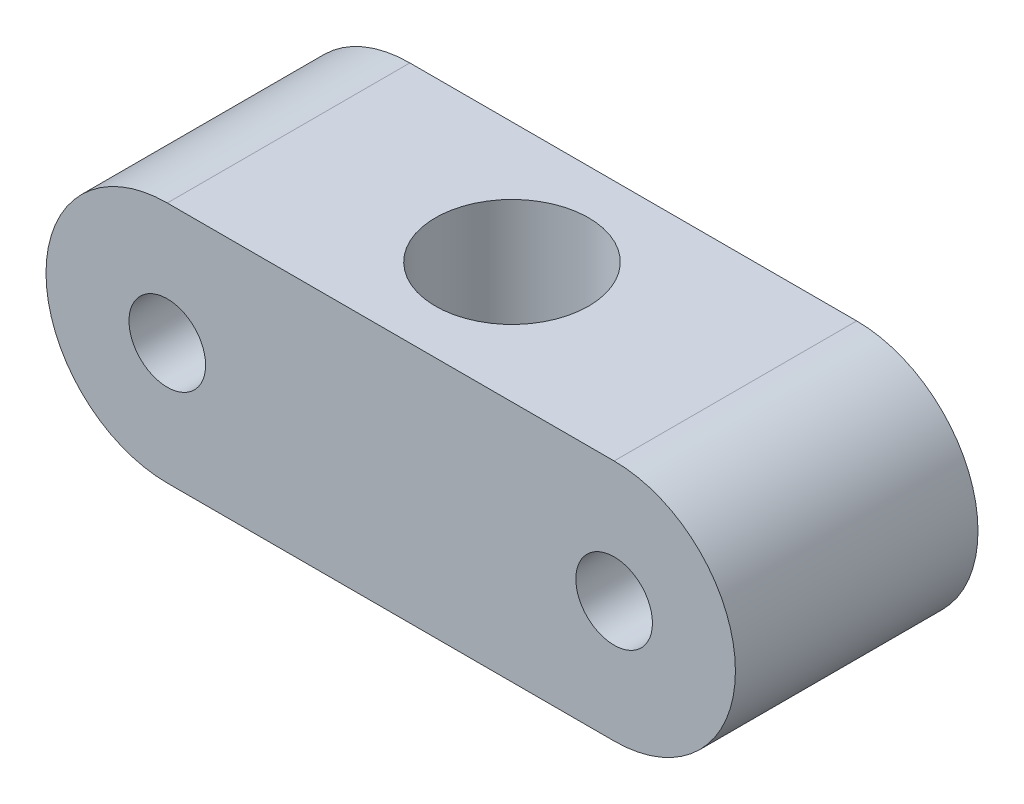
SolidWorks part; units mm, degrees
ref_plane "Front Plane" through (0, 0, 0) normal (0, 0, 1) x (1, 0, 0)
ref_plane "Top Plane" through (0, 0, 0) normal (0, 1, 0) x (1, 0, 0)
ref_plane "Right Plane" through (0, 0, 0) normal (1, 0, 0) x (0, 0, -1)
sketch "Sketch1" plane through (0, 0, 0) normal (0, 0, 1) x (1, 0, 0)
  line L0 (-35, 0) -> (35, 0) construction
  line L1 (-35, 19) -> (35, 19)
  line L2 (-35, -19) -> (35, -19)
  arc A0 (-35, 19) -> (-35, -19) centre (-35, 0) ccw
  arc A1 (35, -19) -> (35, 19) centre (35, 0) ccw
  circle A2 centre (-35, 0) radius 6
  circle A3 centre (35, 0) radius 6
  point P2 (0, 0)
  dimension "D2" = 19
  dimension "D3" = 12
  dimension "D1" = 70
extrude "Boss-Extrude1" add sketch "Sketch1" along normal mid plane 38
sketch "Sketch2" plane through (0, -19, 0) normal (0, -1, 0) x (1, 0, 0)
  circle A0 centre (0, 0) radius 12
  dimension "D1" = 24
extrude "Cut-Extrude1" cut sketch "Sketch2" against normal through all
cosmetic thread "Cosmetic Thread1" parameters "D2"=27
cosmetic thread "Cosmetic Thread2" parameters "D2"=27
